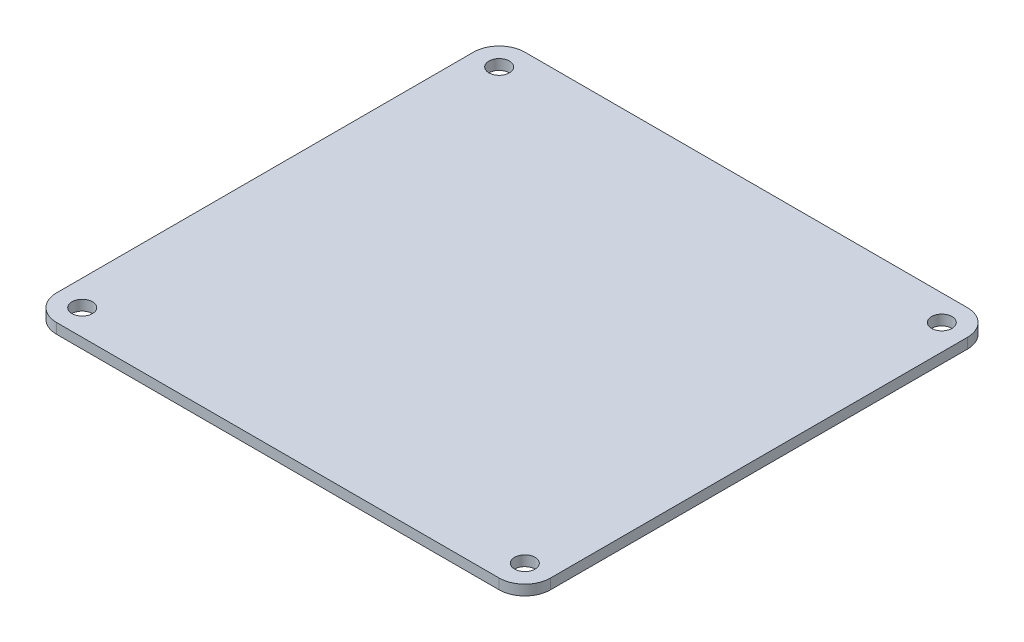
SolidWorks part; units mm, degrees
ref_plane "Front Plane" through (0, 0, 0) normal (0, 0, 1) x (1, 0, 0)
ref_plane "Top Plane" through (0, 0, 0) normal (0, 1, 0) x (1, 0, 0)
ref_plane "Right Plane" through (0, 0, 0) normal (1, 0, 0) x (0, 0, -1)
sketch "Sketch1" plane through (0, 0, 0) normal (0, 1, 0) x (1, 0, 0)
  line L1 (0, 0) -> (77, 0)
  line L2 (0, 0) -> (0, 73)
  line L3 (0, 73) -> (77, 73)
  line L4 (77, 0) -> (77, 73)
  dimension "D1" = 77
  dimension "D2" = 73
extrude "Boss-Extrude1" add sketch "Sketch1" along normal blind 1.6
fillet "Fillet1" radius 4 4 edges at (0, 0.8, 0) (77, 0.8, 0) (77, 0.8, -73) (0, 0.8, -73)
sketch "Sketch3" plane through (0, 1.6, 0) normal (0, 1, 0) x (1, 0, 0)
  line L0 (73, 73) -> (4, 73) construction
  line L1 (77, 4) -> (77, 69) construction
  circle A0 centre (4, 69) radius 1.6
  circle A1 centre (73, 69) radius 1.6
  circle A2 centre (73, 4) radius 1.6
  circle A3 centre (4, 4) radius 1.6
  point P8 (0, 0)
  point P9 (0, 0)
  point P10 (0, 0)
  point P11 (0, 0)
  point P12 (0, 0)
  point P13 (0, 0)
  dimension "D1" = 3.2
  dimension "D2" = 69
  dimension "D3" = 65
  dimension "D4" = 4
  dimension "D5" = 4
extrude "Cut-Extrude1" cut sketch "Sketch3" against normal blind 1.6
